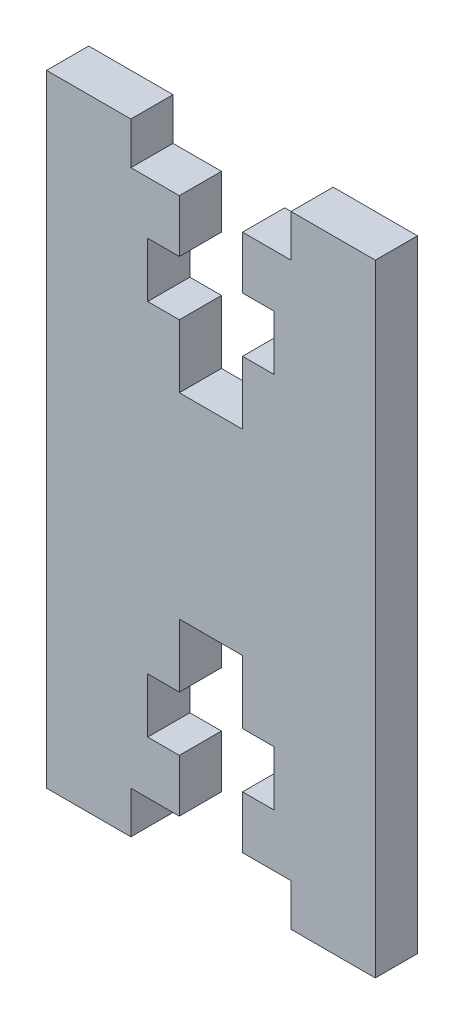
SolidWorks part; units mm, degrees
ref_plane "前视基准面" through (0, 0, 0) normal (0, 0, 1) x (1, 0, 0)
ref_plane "上视基准面" through (0, 0, 0) normal (0, 1, 0) x (1, 0, 0)
ref_plane "右视基准面" through (0, 0, 0) normal (1, 0, 0) x (0, 0, -1)
sketch "草图2" plane through (0, 0, 0) normal (0, 0, 1) x (1, 0, 0)
  line L12 (0.7531, 6.3576) -> (3.0531, 6.3576)
  line L13 (3.0531, -19.1424) -> (3.0531, -21.1424)
  line L16 (3.0531, -21.1424) -> (7.0531, -21.1424)
  line L18 (-4.5469, -21.1424) -> (-8.5469, -21.1424)
  line L19 (-4.5469, -19.1424) -> (-4.5469, -21.1424)
  line L21 (0.7531, -16.6424) -> (0.7531, -19.1424)
  line L22 (-4.5469, -19.1424) -> (-2.2469, -19.1424)
  line L23 (-8.5469, 8.3576) -> (-8.5469, -21.1424)
  line L24 (-4.5469, 8.3576) -> (-8.5469, 8.3576)
  line L25 (-4.5469, 6.3576) -> (-2.2469, 6.3576)
  line L28 (-4.5469, 8.3576) -> (-4.5469, 6.3576)
  line L30 (-3.7469, 3.8576) -> (-3.7469, 1.2576)
  line L31 (-3.7469, 1.2576) -> (-2.2469, 1.2576)
  line L32 (-2.2469, 1.2576) -> (-2.2469, -1.7424)
  line L33 (0.7531, 1.2576) -> (0.7531, -1.7424)
  line L34 (2.2531, 1.2576) -> (0.7531, 1.2576)
  line L35 (2.2531, 3.8576) -> (2.2531, 1.2576)
  line L36 (-2.2469, 3.8576) -> (-3.7469, 3.8576)
  line L37 (-2.2469, -1.7424) -> (0.7531, -1.7424)
  line L38 (0.7531, 3.8576) -> (2.2531, 3.8576)
  line L39 (-2.2469, 3.8576) -> (-2.2469, 6.3576)
  line L40 (0.7531, 3.8576) -> (0.7531, 6.3576)
  line L41 (0.7531, -19.1424) -> (3.0531, -19.1424)
  line L42 (2.2531, -16.6424) -> (2.2531, -14.0424)
  line L43 (2.2531, -14.0424) -> (0.7531, -14.0424)
  line L44 (0.7531, -14.0424) -> (0.7531, -11.0424)
  line L45 (-2.2469, -14.0424) -> (-2.2469, -11.0424)
  line L46 (-3.7469, -14.0424) -> (-2.2469, -14.0424)
  line L47 (-3.7469, -16.6424) -> (-3.7469, -14.0424)
  line L48 (0.7531, -16.6424) -> (2.2531, -16.6424)
  line L49 (0.7531, -11.0424) -> (-2.2469, -11.0424)
  line L50 (-2.2469, -16.6424) -> (-3.7469, -16.6424)
  line L51 (-2.2469, -16.6424) -> (-2.2469, -19.1424)
  line L52 (3.0531, -19.1424) -> (3.0531, 6.3576) construction
  line L53 (3.0531, 6.3576) -> (3.0531, 8.3576)
  line L54 (3.0531, 8.3576) -> (7.0531, 8.3576)
  line L55 (7.0531, 8.3576) -> (7.0531, -21.1424)
  point P5 (-0.7469, -19.1424)
extrude "凸台-拉伸1" add sketch "草图2" along normal blind 2
sketch "草图3" plane through (0, -19.1424, 0) normal (0, -1, 0) x (1, 0, 0)
  line L0 (-2.2469, 1) -> (0.7531, 1)
  line L1 (-2.2469, 2) -> (-2.2469, 0) construction
  line L2 (0.7531, 2) -> (0.7531, 0) construction
  circle A0 centre (-0.7469, 1) radius 1.5
sketch "草图4" plane through (0, 6.3576, 0) normal (0, 1, 0) x (1, 0, 0)
  line L0 (0.7531, -1) -> (-2.2469, -1)
  line L1 (0.7531, -2) -> (0.7531, 0) construction
  line L2 (-2.2469, -2) -> (-2.2469, 0) construction
  circle A0 centre (-0.7469, -1) radius 1.5
